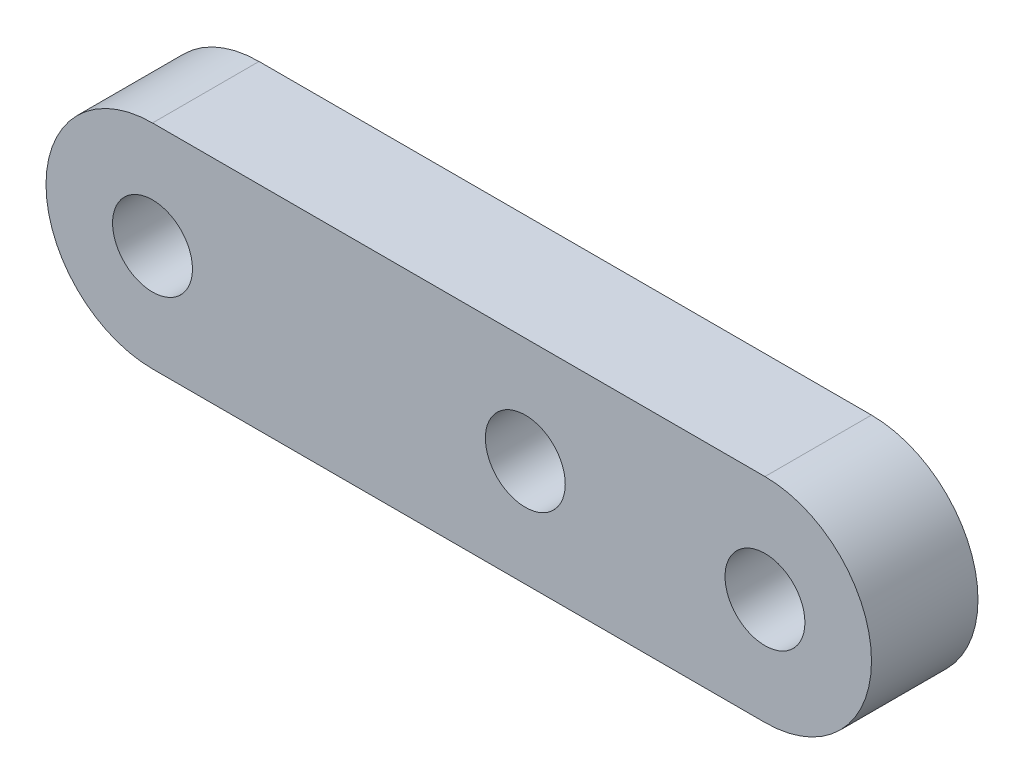
SolidWorks part; units mm, degrees
ref_plane "前视基准面" through (0, 0, 0) normal (0, 0, 1) x (1, 0, 0)
ref_plane "上视基准面" through (0, 0, 0) normal (0, 1, 0) x (1, 0, 0)
ref_plane "右视基准面" through (0, 0, 0) normal (1, 0, 0) x (0, 0, -1)
sketch "草图1" plane through (0, 0, 0) normal (0, 0, 1) x (1, 0, 0)
  line L0 (0, 0) -> (23, 0) construction
  line L2 (0, 4) -> (23, 4)
  line L3 (0, -4) -> (23, -4)
  arc A0 (0, 4) -> (0, -4) centre (0, 0) ccw
  arc A1 (23, -4) -> (23, 4) centre (23, 0) ccw
  circle A2 centre (0, 0) radius 1.5
  circle A3 centre (14, 0) radius 1.5
  circle A4 centre (23, 0) radius 1.5
  point P5 (11.5, 0)
  dimension "D3" = 3
  dimension "D4" = 3
  dimension "D6" = 3
  dimension "D1" = 8
  dimension "D2" = 23
  dimension "D5" = 14
extrude "凸台-拉伸1" add sketch "草图1" along normal blind 4
